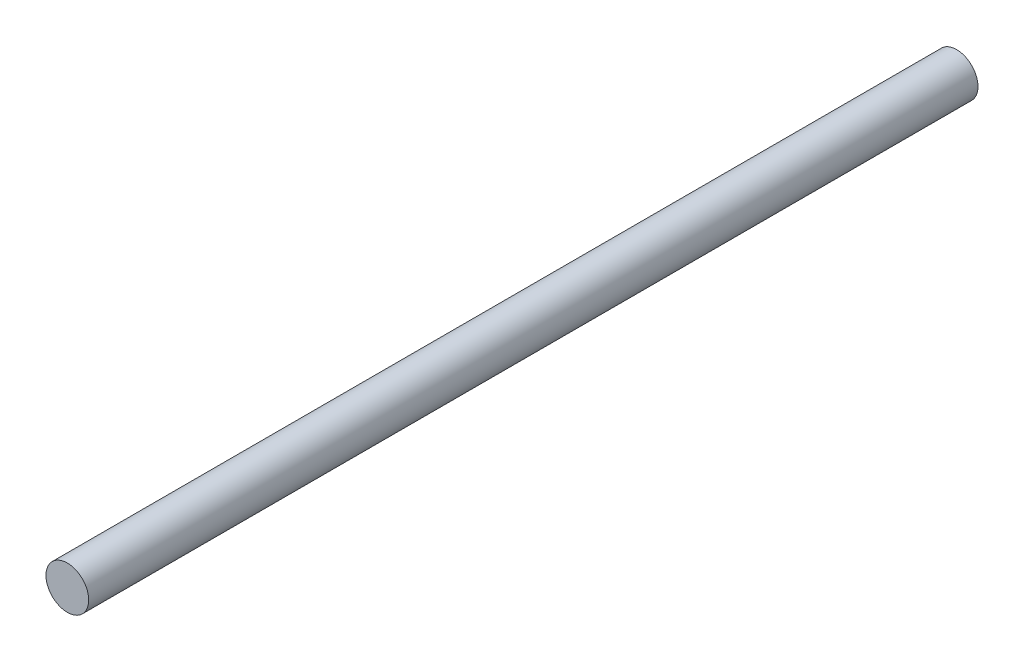
SolidWorks part; units mm, degrees
ref_plane "Front Plane" through (0, 0, 0) normal (0, 0, 1) x (1, 0, 0)
ref_plane "Top Plane" through (0, 0, 0) normal (0, 1, 0) x (1, 0, 0)
ref_plane "Right Plane" through (0, 0, 0) normal (1, 0, 0) x (0, 0, -1)
sketch "Sketch1" plane through (0, 0, 0) normal (0, 0, 1) x (1, 0, 0)
  circle A0 centre (0, 0) radius 1.25
  dimension "D1" = 2.5
extrude "Boss-Extrude1" add sketch "Sketch1" along normal blind 52
